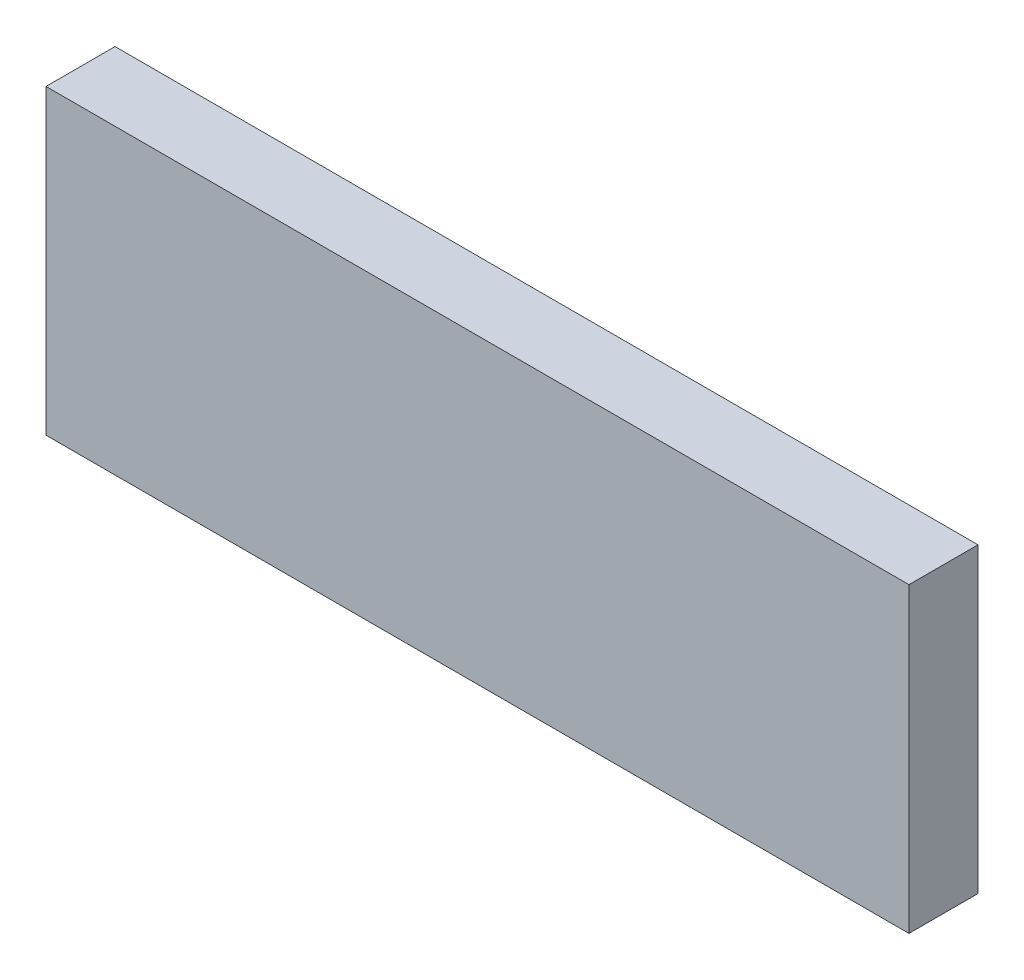
SolidWorks part; units mm, degrees
ref_plane "Front Plane" through (0, 0, 0) normal (0, 0, 1) x (1, 0, 0)
ref_plane "Top Plane" through (0, 0, 0) normal (0, 1, 0) x (1, 0, 0)
ref_plane "Right Plane" through (0, 0, 0) normal (1, 0, 0) x (0, 0, -1)
sketch "Sketch1" plane through (0, 0, 0) normal (0, 0, 1) x (1, 0, 0)
  line L1 (0, 0) -> (200, 0)
  line L2 (0, 0) -> (0, 70)
  line L3 (0, 70) -> (200, 70)
  line L4 (200, 0) -> (200, 70)
  dimension "D1" = 200
  dimension "D2" = 70
extrude "Boss-Extrude1" add sketch "Sketch1" along normal blind 16
